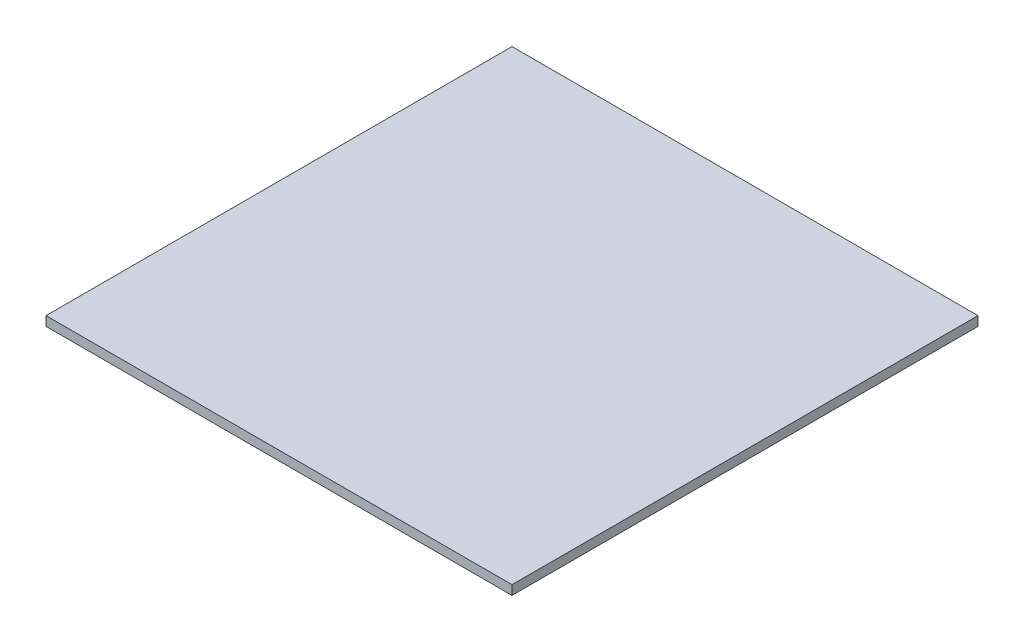
SolidWorks part; units mm, degrees
material "玻璃"
ref_plane "前视基准面" through (0, 0, 0) normal (0, 0, 1) x (1, 0, 0)
ref_plane "上视基准面" through (0, 0, 0) normal (0, 1, 0) x (1, 0, 0)
ref_plane "右视基准面" through (0, 0, 0) normal (1, 0, 0) x (0, 0, -1)
sketch "草图1" plane through (0, 0, 0) normal (0, 1, 0) x (1, 0, 0)
  line L1 (0, 0) -> (200, 0)
  line L2 (0, 0) -> (0, -200)
  line L3 (0, -200) -> (200, -200)
  line L4 (200, 0) -> (200, -200)
  dimension "D1" = 200
  dimension "D2" = 200
extrude "凸台-拉伸1" add sketch "草图1" along normal blind 4
